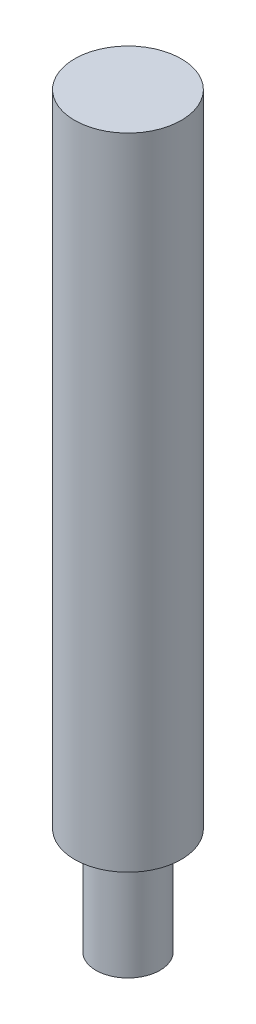
SolidWorks part; units mm, degrees
ref_plane "Front Plane" through (0, 0, 0) normal (0, 0, 1) x (1, 0, 0)
ref_plane "Top Plane" through (0, 0, 0) normal (0, 1, 0) x (1, 0, 0)
ref_plane "Right Plane" through (0, 0, 0) normal (1, 0, 0) x (0, 0, -1)
sketch "Sketch1" plane through (0, 0, 0) normal (0, 1, 0) x (1, 0, 0)
  circle A0 centre (0, 0) radius 2.5
  dimension "D1" = 5
extrude "Boss-Extrude1" add sketch "Sketch1" along normal blind 30
sketch "Sketch2" plane through (0, 0, 0) normal (0, -1, 0) x (-1, 0, 0)
  circle A0 centre (0, 0) radius 1.5
  dimension "D1" = 3
extrude "Boss-Extrude2" add sketch "Sketch2" along normal blind 5
